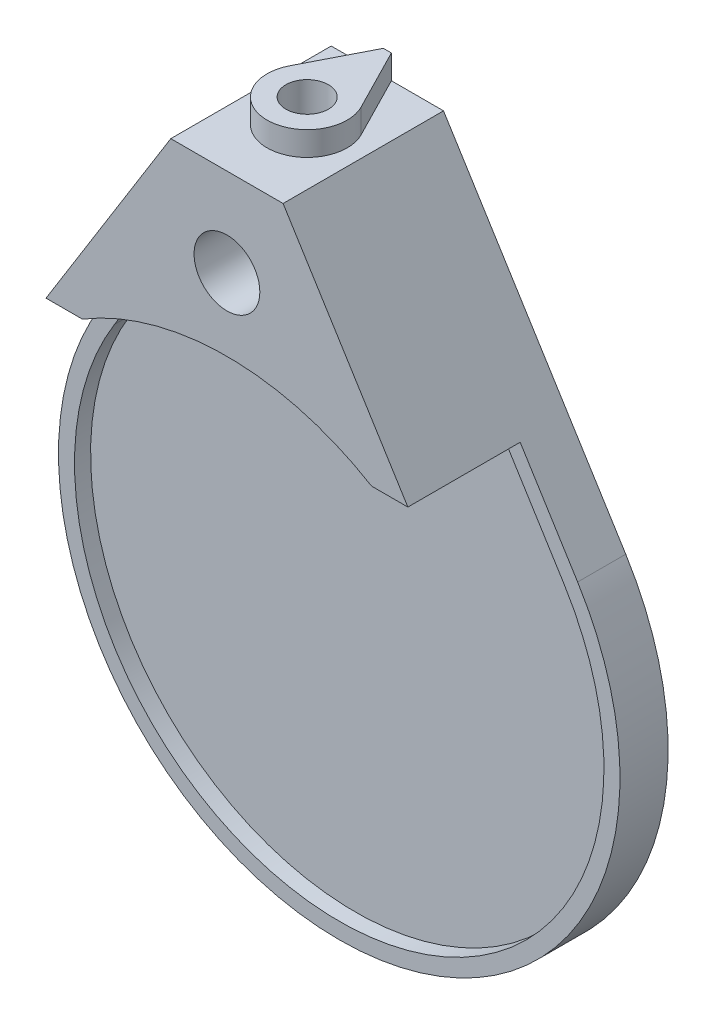
SolidWorks part; units mm, degrees
ref_plane "Alzado" through (0, 0, 0) normal (0, 0, 1) x (1, 0, 0)
ref_plane "Planta" through (0, 0, 0) normal (0, 1, 0) x (1, 0, 0)
ref_plane "Vista lateral" through (0, 0, 0) normal (1, 0, 0) x (0, 0, -1)
sketch "Croquis1" plane through (0, 0, 0) normal (0, 0, 1) x (1, 0, 0)
  circle A0 centre (0, 0) radius 35
  dimension "D1" = 70
extrude "Saliente-Extruir1" add sketch "Croquis1" along normal blind 4
sketch "Croquis2" plane through (0, 0, 4) normal (0, 0, 1) x (1, 0, 0)
  line L0 (29.717, 18.4906) -> (7, 55)
  line L1 (7, 55) -> (-7, 55)
  line L2 (-7, 55) -> (-29.717, 18.4906)
  line L3 (0, 0) -> (0, 55) construction
  circle A0 centre (0, 0) radius 35 construction
  arc A2 (29.717, 18.4906) -> (-29.717, 18.4906) centre (0, 0) ccw
  circle A4 centre (0, 44) radius 4.1
  point P4 (0, 46.3268)
  point P7 (0, 68.6364)
  point P15 (8.9978, 53.0867)
  point P16 (8, 55.4)
  point P17 (7.0707, 55)
  point P18 (0, 59.4196)
  dimension "D1" = 8.2
  dimension "D2" = 11
  dimension "D5" = 55
  dimension "D6" = 14
extrude "Saliente-Extruir2" add sketch "Croquis2" against normal blind 4
sketch "Croquis4" plane through (0, 0, 4) normal (0, 0, 1) x (1, 0, 0)
  line L3 (29.717, 18.4906) -> (7, 55)
  line L4 (7, 55) -> (-7, 55)
  line L5 (-7, 55) -> (-29.717, 18.4906)
  line L6 (29.717, 18.4906) -> (7, 55)
  line L7 (7, 55) -> (-7, 55)
  line L8 (-7, 55) -> (-29.717, 18.4906)
  circle A1 centre (0, 44) radius 4.1
  circle A2 centre (0, 44) radius 4.1
  arc A3 (29.717, 18.4906) -> (-29.717, 18.4906) centre (0, 0) ccw
  arc A4 (29.717, 18.4906) -> (-29.717, 18.4906) centre (0, 0) ccw
  dimension "D1" = 0
  dimension "D2" = 0
extrude "Saliente-Extruir5" add sketch "Croquis4" along normal blind 16
sketch "Croquis7" plane through (0, 0, 4) normal (0, 0, 1) x (1, 0, 0)
  line L1 (-35, -30) -> (35, -30)
  line L2 (-35, -30) -> (-35, 30)
  line L3 (-35, 30) -> (35, 30)
  line L4 (35, -30) -> (35, 30)
  line L5 (0, 30) -> (0, -30) construction
  line L6 (-35, 0) -> (35, 0) construction
  arc A0 (-29.717, 18.4906) -> (29.717, 18.4906) centre (0, 0) ccw construction
  point P0 (0, 0)
  point P4 (-39.2069, 27.5)
  point P5 (-35, 0)
  dimension "D1" = 60
extrude "Cortar-Extruir2" cut sketch "Croquis7" along normal through all
sketch "Croquis8" plane through (0, 0, 4) normal (0, 0, 1) x (1, 0, 0)
  line L2 (29.717, 18.4906) -> (22.5556, 30) construction
  line L3 (-22.5556, 30) -> (-29.717, 18.4906) construction
  line L4 (-20.8574, 28.9434) -> (-28.0189, 17.434)
  line L6 (29.717, 18.4906) -> (22.5556, 30)
  line L7 (-22.5556, 30) -> (-29.717, 18.4906)
  line L8 (28.0189, 17.434) -> (20.8574, 28.9434)
  line L13 (-20.8574, 28.9434) -> (-20.2, 30)
  line L14 (20.8574, 28.9434) -> (20.2, 30)
  line L15 (-20.2, 30) -> (-22.5556, 30)
  line L16 (-18.0278, 30) -> (-22.5556, 30) construction
  line L17 (20.2, 30) -> (22.5556, 30)
  line L18 (22.5556, 30) -> (18.0278, 30) construction
  arc A1 (-29.717, 18.4906) -> (29.717, 18.4906) centre (0, 0) ccw construction
  arc A2 (-29.717, 18.4906) -> (29.717, 18.4906) centre (0, 0) ccw
  arc A3 (-28.0189, 17.434) -> (28.0189, 17.434) centre (0, 0) ccw
  point P11 (21.7581, 27.5)
  dimension "D1" = 2
extrude "Saliente-Extruir6" add sketch "Croquis8" along normal blind 2
sketch "Croquis12" plane through (0, 55, 0) normal (0, 1, 0) x (1, 0, 0)
  line L0 (0, 0) -> (0, -20) construction
  line L1 (7, -20) -> (-7, -20) construction
  line L2 (-4.4512, -7.7226) -> (-0.5, 0)
  line L3 (7, 0) -> (-7, 0) construction
  line L4 (0.5, 0) -> (4.4512, -7.7226)
  line L5 (-0.5, 0) -> (0.5, 0)
  arc A0 (-4.4512, -7.7226) -> (4.4512, -7.7226) centre (0, -10) ccw
  circle A1 centre (0, -10) radius 2.65
  point P14 (0.8063, 0)
  dimension "D1" = 10
  dimension "D2" = 5.3
  dimension "D3" = 1
extrude "Saliente-Extruir8" add sketch "Croquis12" along normal blind 3
sketch "Croquis13" plane through (0, 58, 0) normal (0, 1, 0) x (1, 0, 0)
  circle A0 centre (0, -10) radius 2.65 construction
  circle A1 centre (0, -10) radius 2.65
extrude "Cortar-Extruir5" cut sketch "Croquis13" against normal blind 16
